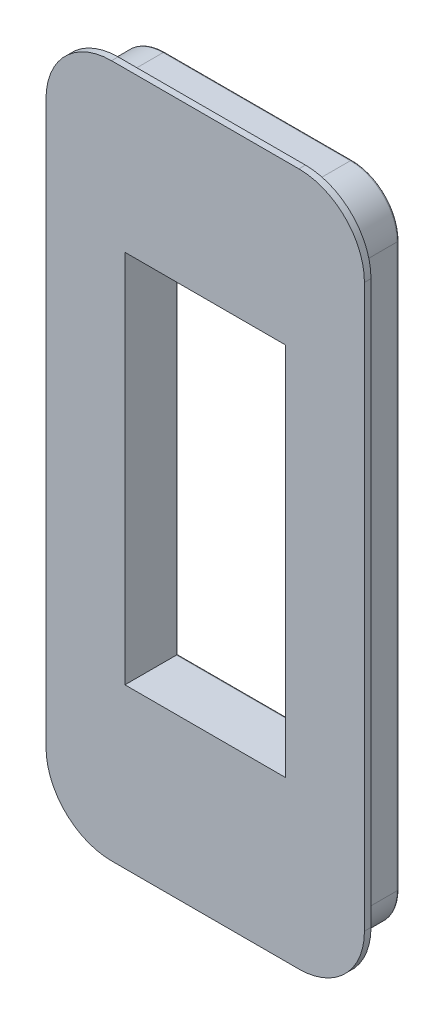
SolidWorks part; units mm, degrees
ref_plane "Front" through (0, 0, 0) normal (0, 0, 1) x (1, 0, 0)
ref_plane "Top" through (0, 0, 0) normal (0, 1, 0) x (1, 0, 0)
ref_plane "Right" through (0, 0, 0) normal (1, 0, 0) x (0, 0, -1)
sketch "Sketch4" plane through (0, 0, 0) normal (0, 0, 1) x (1, 0, 0)
  line L0 (0, 0) -> (0, 11.5327)
  line L1 (15, -35) -> (-15, -35)
  line L2 (15, -35) -> (15, 35)
  line L3 (15, 35) -> (-15, 35)
  line L4 (-15, -35) -> (-15, 35)
  line L5 (15, -35) -> (-15, 35) construction
  line L6 (15, 35) -> (-15, -35) construction
  line L7 (0, 11.5327) -> (0, 0)
  line L8 (0, 0) -> (7.2917, 0)
  line L10 (8.5714, -20) -> (-8.5714, -20)
  line L11 (8.5714, -20) -> (8.5714, 20)
  line L12 (8.5714, 20) -> (-8.5714, 20)
  line L13 (-8.5714, -20) -> (-8.5714, 20)
  line L14 (8.5714, -20) -> (-8.5714, 20) construction
  line L15 (8.5714, 20) -> (-8.5714, -20) construction
  circle A0 centre (-7.5, 28) radius 3.5
  circle A1 centre (7.5, 28) radius 3.5
  circle A2 centre (7.5, -28) radius 3.5
  circle A3 centre (-7.5, -28) radius 3.5
  point P0 (0, 0)
  dimension "D3" = 7
  dimension "D1" = 30
  dimension "D2" = 70
  dimension "D4" = 28
  dimension "D5" = 7.5
  dimension "D6" = 40
extrude "Boss-Extrude1" add sketch "Sketch4" along normal blind 5 contours L4 L1 L2 L3 A1 A0 L10 L13 L12 L11 A2 A3
sketch "Sketch5" plane through (0, 0, 5) normal (0, 0, 1) x (1, 0, 0)
  line L0 (-17, -37) -> (17, -37)
  line L1 (-15, 35) -> (15, 35)
  line L2 (-15, 35) -> (-15, -35)
  line L3 (-15, -35) -> (15, -35)
  line L4 (15, 35) -> (15, -35)
  line L5 (-15, 35) -> (15, -35) construction
  line L6 (-15, -35) -> (15, 35) construction
  line L7 (17, 37) -> (17, -37)
  line L8 (-17, 37) -> (17, 37)
  line L9 (-17, 37) -> (-17, -37)
  line L11 (-8.5714, 20) -> (8.5714, 20)
  line L12 (-8.5714, 20) -> (-8.5714, -20)
  line L13 (-8.5714, -20) -> (8.5714, -20)
  line L14 (8.5714, 20) -> (8.5714, -20)
  line L15 (-8.5714, 20) -> (8.5714, -20) construction
  line L16 (-8.5714, -20) -> (8.5714, 20) construction
  circle A0 centre (-7.5, 28) radius 3.5
  circle A1 centre (7.5, 28) radius 3.5
  circle A2 centre (-7.5, -28) radius 3.5
  circle A3 centre (7.5, -28) radius 3.5
  point P0 (0, 0)
  point P23 (0, 0)
  circle M1 centre (7.5, 28) radius 3.5
  circle M2 centre (-7.5, 28) radius 3.5
  line M3 (-15, 35) -> (-15, -35)
  line M4 (-15, -35) -> (15, -35)
  line M5 (15, -35) -> (15, 35)
  line M6 (15, 35) -> (-15, 35)
  line M7 (8.5714, -20) -> (-8.5714, -20)
  line M8 (-8.5714, -20) -> (-8.5714, 20)
  line M9 (-8.5714, 20) -> (8.5714, 20)
  line M10 (8.5714, 20) -> (8.5714, -20)
  circle M11 centre (7.5, -28) radius 3.5
  circle M12 centre (-7.5, -28) radius 3.5
  dimension "D1" = 2
extrude "Boss-Extrude2" add sketch "Sketch5" along normal blind 0.7 contours M6 M3 M4 M5 M2 M10 M7 M8 M9 M12 M11 M1 | L8 L9 L0 L7 M3 M6 M5 M4 | M11 | M12 | M1 | M2
fillet "Fillet1" radius 5 4 edges at (15, -35, 2.5) (-15, -35, 2.5) (-15, 35, 2.5) (15, 35, 2.5)
fillet "Fillet2" radius 0.2 16 edges at (-4, -28, 0) (11, -28, 0) (-8.5714, 0, 0) (0, 20, 0) (8.5714, 0, 0) (0, -20, 0) (13.5355, 33.5355, 0) (0, 35, 0) (-13.5355, 33.5355, 0) (-15, 0, 0) (-13.5355, -33.5355, 0) (0, -35, 0) (13.5355, -33.5355, 0) (15, 0, 0) (-4, 28, 0) (11, 28, 0)
fillet "Fillet3" radius 7 4 edges at (-17, -37, 5.35) (17, -37, 5.35) (17, 37, 5.35) (-17, 37, 5.35)
